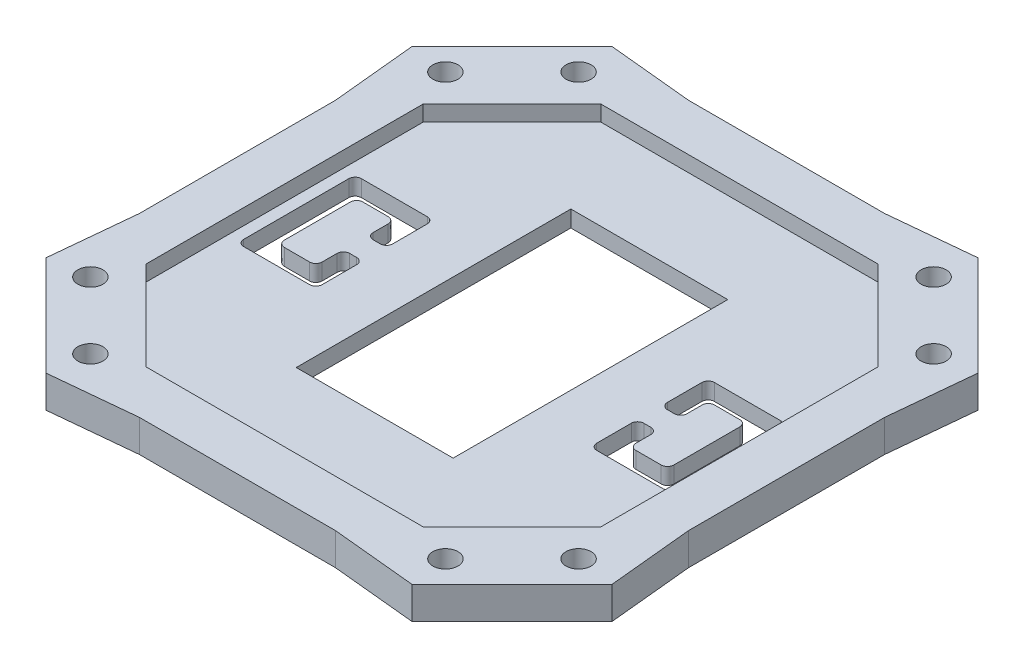
SolidWorks part; units mm, degrees
ref_plane "Front Plane" through (0, 0, 0) normal (0, 0, 1) x (1, 0, 0)
ref_plane "Top Plane" through (0, 0, 0) normal (0, 1, 0) x (1, 0, 0)
ref_plane "Right Plane" through (0, 0, 0) normal (1, 0, 0) x (0, 0, -1)
sketch "Sketch1" plane through (0, 0, 0) normal (0, 1, 0) x (1, 0, 0)
  line L0 (-35, 12.5) -> (-36.0623, 23.3344)
  line L1 (-35, 35) -> (35, 35) construction
  line L2 (-35, 35) -> (-35, -35) construction
  line L3 (-35, -35) -> (35, -35) construction
  line L4 (35, 35) -> (35, -35) construction
  line L5 (-35, 35) -> (35, -35) construction
  line L6 (-35, -35) -> (35, 35) construction
  line L7 (-36.0623, 23.3344) -> (-23.3344, 36.0623)
  line L8 (-23.3344, 36.0623) -> (-12.5, 35)
  line L9 (36.0623, 23.3344) -> (35, 12.5)
  line L10 (23.3344, 36.0623) -> (36.0623, 23.3344)
  line L11 (12.5, 35) -> (23.3344, 36.0623)
  line L12 (23.3344, -36.0623) -> (12.5, -35)
  line L13 (36.0623, -23.3344) -> (23.3344, -36.0623)
  line L14 (35, -12.5) -> (36.0623, -23.3344)
  line L15 (-36.0623, -23.3344) -> (-35, -12.5)
  line L16 (-23.3344, -36.0623) -> (-36.0623, -23.3344)
  line L17 (-12.5, -35) -> (-23.3344, -36.0623)
  line L18 (-35, 12.5) -> (-35, -12.5)
  line L19 (-12.5, 35) -> (12.5, 35)
  line L20 (35, 12.5) -> (35, -12.5)
  line L21 (12.5, -35) -> (-12.5, -35)
  line L22 (20.506, 33.2339) -> (33.2339, 20.506) construction
  line L23 (33.2339, -20.506) -> (20.506, -33.2339) construction
  line L24 (-20.506, -33.2339) -> (-33.2339, -20.506) construction
  line L25 (-33.2339, 20.506) -> (-20.506, 33.2339) construction
  circle A0 centre (22.6273, 31.1126) radius 1.6
  circle A1 centre (31.1126, 22.6273) radius 1.6
  circle A2 centre (31.1126, -22.6273) radius 1.6
  circle A3 centre (22.6273, -31.1126) radius 1.6
  circle A4 centre (-22.6273, -31.1126) radius 1.6
  circle A5 centre (-31.1126, -22.6273) radius 1.6
  circle A6 centre (-31.1126, 22.6273) radius 1.6
  circle A7 centre (-22.6273, 31.1126) radius 1.6
  point P0 (0, 0)
  point P11 (-29.6984, 29.6984)
  point P26 (0, 0)
  point P51 (0, 0)
  dimension "D9" = 3.2
  dimension "D1" = 70
  dimension "D2" = 5.6
  dimension "D3" = 5.6
  dimension "D4" = 22.5
  dimension "D5" = 22.5
  dimension "D6" = 18
  dimension "D10" = 6
  dimension "D11" = 6
  dimension "D8" = 4
  dimension "D7" = 4
  dimension "D12" = 4
extrude "Boss-Extrude1" add sketch "Sketch1" along normal blind 4.1
sketch "Sketch2" plane through (0, 4.1, 0) normal (0, 1, 0) x (1, 0, 0)
  line L0 (35, -12.5) -> (35, 12.5) construction
  line L1 (-17.6688, 29) -> (17.6688, 29)
  line L2 (-29, 17.6688) -> (-29, -17.6688)
  line L3 (-17.6688, -29) -> (17.6688, -29)
  line L4 (29, 17.6688) -> (29, -17.6688)
  line L5 (-23.3344, 23.3344) -> (23.3344, -23.3344) construction
  line L6 (-23.3344, -23.3344) -> (23.3344, 23.3344) construction
  line L7 (12.5, 35) -> (-12.5, 35) construction
  line L8 (-35, 12.5) -> (-35, -12.5) construction
  line L9 (-12.5, -35) -> (12.5, -35) construction
  line L13 (-16.9704, 29.6984) -> (-29.6984, 16.9704)
  line L14 (-17.6688, 29) -> (-29, 17.6688)
  line L16 (29.6984, 16.9704) -> (16.9704, 29.6984)
  line L17 (29, 17.6688) -> (17.6688, 29)
  line L19 (16.9704, -29.6984) -> (29.6984, -16.9704)
  line L20 (17.6688, -29) -> (29, -17.6688)
  line L22 (-29.6984, -16.9704) -> (-16.9704, -29.6984)
  line L23 (-29, -17.6688) -> (-17.6688, -29)
  point P0 (0, 0)
  point P8 (29, 0)
  dimension "D1" = 6
  dimension "D2" = 6
  dimension "D7" = 6
  dimension "D8" = 6
  dimension "D3" = 9
  dimension "D4" = 9
  dimension "D5" = 9
  dimension "D6" = 9
extrude "Cut-Extrude1" cut sketch "Sketch2" against normal blind 2
sketch "Sketch3" plane through (0, 2.1, 0) normal (0, 1, 0) x (1, 0, 0)
  line L0 (29, 0) -> (-29, 0) construction
  line L1 (-29, 17.6688) -> (-29, -17.6688) construction
  line L2 (-27.5, 6.7) -> (-27.5, -6.7)
  line L3 (-26.7, -7.5) -> (-18.3, -7.5)
  line L4 (-17.5, -6.7) -> (-17.5, -2.3)
  line L5 (-18.3, -1.5) -> (-19.2, -1.5)
  line L6 (-20, -2.3) -> (-20, -4.2)
  line L7 (-20.8, -5) -> (-24.02, -5)
  line L8 (-24.82, -4.2) -> (-24.82, 4.22)
  line L9 (-24.02, 5.02) -> (-20.8, 5.02)
  line L10 (-20, 4.22) -> (-20, 2.3)
  line L11 (-19.2, 1.5) -> (-18.3, 1.5)
  line L12 (-17.5, 2.3) -> (-17.5, 6.7)
  line L13 (-18.3, 7.5) -> (-26.7, 7.5)
  line L14 (0, 0) -> (0, -22.6407) construction
  line L15 (18.3, 7.5) -> (26.7, 7.5)
  line L16 (17.5, 2.3) -> (17.5, 6.7)
  line L17 (19.2, 1.5) -> (18.3, 1.5)
  line L18 (20, 4.22) -> (20, 2.3)
  line L19 (24.02, 5.02) -> (20.8, 5.02)
  line L20 (24.82, -4.2) -> (24.82, 4.22)
  line L21 (20.8, -5) -> (24.02, -5)
  line L22 (20, -2.3) -> (20, -4.2)
  line L23 (18.3, -1.5) -> (19.2, -1.5)
  line L24 (17.5, -6.7) -> (17.5, -2.3)
  line L25 (26.7, -7.5) -> (18.3, -7.5)
  line L26 (27.5, 6.7) -> (27.5, -6.7)
  arc A0 (26.7, -7.5) -> (27.5, -6.7) centre (26.7, -6.7) ccw
  arc A1 (17.5, -6.7) -> (18.3, -7.5) centre (18.3, -6.7) ccw
  arc A2 (18.3, -1.5) -> (17.5, -2.3) centre (18.3, -2.3) ccw
  arc A3 (20, -2.3) -> (19.2, -1.5) centre (19.2, -2.3) ccw
  arc A4 (20.8, -5) -> (20, -4.2) centre (20.8, -4.2) cw
  arc A5 (24.82, -4.2) -> (24.02, -5) centre (24.02, -4.2) cw
  arc A6 (24.02, 5.02) -> (24.82, 4.22) centre (24.02, 4.22) cw
  arc A7 (20, 4.22) -> (20.8, 5.02) centre (20.8, 4.22) cw
  arc A8 (19.2, 1.5) -> (20, 2.3) centre (19.2, 2.3) ccw
  arc A9 (17.5, 2.3) -> (18.3, 1.5) centre (18.3, 2.3) ccw
  arc A10 (26.7, 7.5) -> (27.5, 6.7) centre (26.7, 6.7) cw
  arc A11 (18.3, 7.5) -> (17.5, 6.7) centre (18.3, 6.7) ccw
  arc A12 (-17.5, 6.7) -> (-18.3, 7.5) centre (-18.3, 6.7) ccw
  arc A13 (-20, 2.3) -> (-19.2, 1.5) centre (-19.2, 2.3) ccw
  arc A14 (-20.8, 5.02) -> (-20, 4.22) centre (-20.8, 4.22) cw
  arc A15 (-24.82, 4.22) -> (-24.02, 5.02) centre (-24.02, 4.22) cw
  arc A16 (-24.02, -5) -> (-24.82, -4.2) centre (-24.02, -4.2) cw
  arc A17 (-20, -4.2) -> (-20.8, -5) centre (-20.8, -4.2) cw
  arc A18 (-19.2, -1.5) -> (-20, -2.3) centre (-19.2, -2.3) ccw
  arc A19 (-17.5, -2.3) -> (-18.3, -1.5) centre (-18.3, -2.3) ccw
  arc A20 (-18.3, -7.5) -> (-17.5, -6.7) centre (-18.3, -6.7) ccw
  arc A21 (-18.3, 1.5) -> (-17.5, 2.3) centre (-18.3, 2.3) ccw
  arc A22 (-27.5, -6.7) -> (-26.7, -7.5) centre (-26.7, -6.7) ccw
  arc A23 (-27.5, 6.7) -> (-26.7, 7.5) centre (-26.7, 6.7) cw
  point P21 (-27.5, 0)
  point P34 (27.5, -7.5)
  point P37 (17.5, -7.5)
  point P40 (17.5, -1.5)
  point P43 (20, -1.5)
  point P46 (20, -5)
  point P49 (24.82, -5)
  point P52 (24.82, 5.02)
  point P55 (20, 5.02)
  point P58 (20, 1.5)
  point P61 (17.5, 1.5)
  point P64 (27.5, 7.5)
  point P67 (17.5, 7.5)
  point P70 (-17.5, 7.5)
  point P73 (-20, 1.5)
  point P76 (-20, 5.02)
  point P79 (-24.82, 5.02)
  point P82 (-24.82, -5)
  point P85 (-20, -5)
  point P88 (-20, -1.5)
  point P91 (-17.5, -1.5)
  point P94 (-17.5, -7.5)
  point P97 (-17.5, 1.5)
  point P100 (-27.5, -7.5)
  point P103 (-27.5, 7.5)
  dimension "D9" = 0.8
  dimension "D1" = 10
  dimension "D2" = 2.68
  dimension "D3" = 10.02
  dimension "D4" = 15
  dimension "D5" = 6
  dimension "D6" = 2.5
  dimension "D7" = 17.5
  dimension "D8" = 2.5
extrude "Cut-Extrude2" cut sketch "Sketch3" against normal through all
sketch "Sketch4" plane through (0, 2.1, 0) normal (0, 1, 0) x (1, 0, 0)
  line L1 (-10, 17.5) -> (10, 17.5)
  line L2 (-10, 17.5) -> (-10, -17.5)
  line L3 (-10, -17.5) -> (10, -17.5)
  line L4 (10, 17.5) -> (10, -17.5)
  line L5 (-10, 17.5) -> (10, -17.5) construction
  line L6 (-10, -17.5) -> (10, 17.5) construction
  point P0 (0, 0)
  dimension "D1" = 20
  dimension "D2" = 35
extrude "Cut-Extrude3" cut sketch "Sketch4" against normal through all
